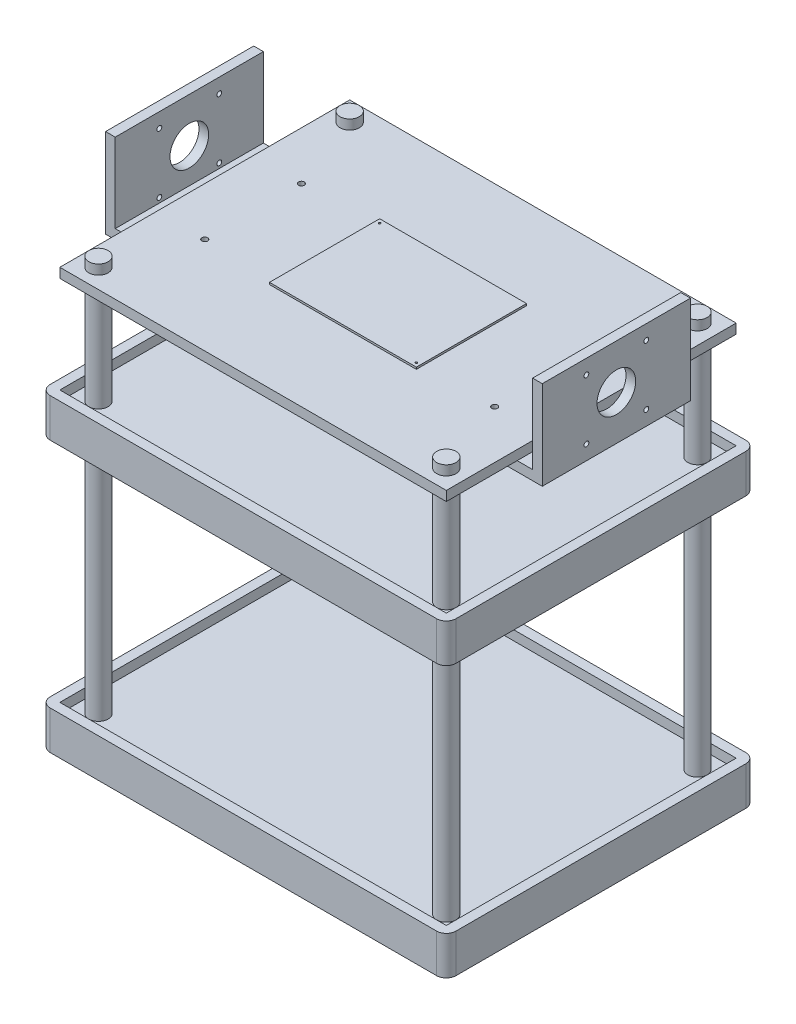
SolidWorks part; units mm, degrees
ref_plane "Front Plane" through (0, 0, 0) normal (0, 0, 1) x (1, 0, 0)
ref_plane "Top Plane" through (0, 0, 0) normal (0, 1, 0) x (1, 0, 0)
ref_plane "Right Plane" through (0, 0, 0) normal (1, 0, 0) x (0, 0, -1)
sketch "Sketch1" plane through (0, 0, 0) normal (0, 1, 0) x (1, 0, 0)
  line L1 (-100, 75) -> (100, 75)
  line L2 (-100, 75) -> (-100, -75)
  line L3 (-100, -75) -> (100, -75)
  line L4 (100, 75) -> (100, -75)
  line L5 (-100, 75) -> (100, -75) construction
  line L6 (-100, -75) -> (100, 75) construction
  point P0 (0, 0)
  dimension "D1" = 200
  dimension "D2" = 150
extrude "Boss-Extrude1" add sketch "Sketch1" along normal blind 5
sketch "Sketch2" plane through (0, 5, 0) normal (0, 1, 0) x (1, 0, 0)
  line L0 (-100, 75) -> (-100, -75) construction
  line L1 (100, 75) -> (-100, 75) construction
  line L2 (0, 73.0671) -> (0, 83.6614) construction
  line L3 (0, 83.6614) -> (0, -94.4748) construction
  line L4 (-110.8687, 0) -> (113.9791, 0) construction
  circle A0 centre (-90, 65) radius 5
  circle A1 centre (90, 65) radius 5
  circle A2 centre (90, -65) radius 5
  circle A3 centre (-90, -65) radius 5
  dimension "D1" = 10
  dimension "D2" = 10
  dimension "D3" = 10
extrude "Cut-Extrude1" cut sketch "Sketch2" against normal blind 10
ref_plane "Plane1" through (0, 140, 0) normal (0, 1, 0) x (1, 0, 0)
sketch "Sketch3" plane through (0, 140, 0) normal (0, 1, 0) x (1, 0, 0)
  line L1 (-100, 75) -> (100, 75)
  line L2 (-100, 75) -> (-100, -75)
  line L3 (-100, -75) -> (100, -75)
  line L4 (100, 75) -> (100, -75)
  line L5 (-100, 75) -> (100, -75) construction
  line L6 (-100, -75) -> (100, 75) construction
  circle A0 centre (-90, 65) radius 5
  circle A1 centre (90, 65) radius 5
  circle A2 centre (-90, -65) radius 5
  circle A3 centre (90, -65) radius 5
  point P0 (0, 0)
extrude "Boss-Extrude2" add sketch "Sketch3" along normal blind 5 separate body
ref_plane "Plane4" through (0, 200, 0) normal (0, 1, 0) x (1, 0, 0)
sketch "Sketch4" plane through (0, 200, 0) normal (0, 1, 0) x (1, 0, 0)
  line L1 (-100, 75) -> (100, 75)
  line L2 (-100, 75) -> (-100, -75)
  line L3 (-100, -75) -> (100, -75)
  line L4 (100, 75) -> (100, -75)
  line L5 (-100, 75) -> (100, -75) construction
  line L6 (-100, -75) -> (100, 75) construction
  circle A0 centre (-90, 65) radius 5
  circle A1 centre (90, 65) radius 5
  circle A2 centre (90, -65) radius 5
  circle A3 centre (-90, -65) radius 5
  point P1 (0, 0)
extrude "Boss-Extrude3" add sketch "Sketch4" along normal blind 5 separate body
sketch "Sketch5" plane through (0, 205, 0) normal (0, 1, 0) x (1, 0, 0)
  circle A0 centre (-90, -65) radius 5
sketch "Sketch17" plane through (0, 200, 0) normal (0, -1, 0) x (1, 0, 0)
  circle A0 centre (-90, -65) radius 5.3637
sketch "Sketch21" plane through (0, 5, 0) normal (0, 1, 0) x (1, 0, 0)
  circle A0 centre (-90, -65) radius 5
  circle A1 centre (-90, 65) radius 5
  circle A2 centre (90, 65) radius 5
  circle A3 centre (90, -65) radius 5
  dimension "D1" = 10
  dimension "D2" = 10
  dimension "D3" = 10
  dimension "D4" = 10
extrude "Boss-Extrude13" add sketch "Sketch21" along normal blind 205
sketch "Sketch22" plane through (0, 5, 0) normal (0, 1, 0) x (1, 0, 0)
  circle A0 centre (-90, 65) radius 5
  circle A1 centre (-90, -65) radius 5
  circle A2 centre (90, -65) radius 5
  circle A3 centre (90, 65) radius 5
  dimension "D1" = 10
  dimension "D2" = 10
  dimension "D3" = 10
  dimension "D4" = 10
extrude "Boss-Extrude14" add sketch "Sketch22" against normal blind 15
sketch "Sketch23" plane through (0, 205, 0) normal (0, 1, 0) x (1, 0, 0)
  line L0 (-100, 75) -> (-100, -75) construction
  line L1 (-140.155, 0) -> (119.4256, 0) construction
  line L2 (0, -2.75) -> (0, 2.75) construction
  circle A0 centre (-75, 25) radius 1.5
  circle A1 centre (-75, -25) radius 1.5
  circle A2 centre (75, -25) radius 1.5
  circle A3 centre (75, 25) radius 1.5
  dimension "D1" = 3
  dimension "D2" = 25
  dimension "D3" = 25
extrude "Cut-Extrude2" cut sketch "Sketch23" against normal blind 10
sketch "Sketch27" plane through (0, 205, 0) normal (0, 1, 0) x (1, 0, 0)
  line L0 (-38, 28.5) -> (38, -28.5) construction
  line L5 (-38, -28.5) -> (38, 28.5) construction
  line L7 (-38, 28.5) -> (38, 28.5)
  line L8 (-38, 28.5) -> (-38, -28.5)
  line L9 (-38, -28.5) -> (38, -28.5)
  line L10 (38, 28.5) -> (38, -28.5)
  circle A0 centre (-36, 26.5) radius 0.5
  circle A1 centre (36, -26.5) radius 0.5
  point P0 (-6.164, -10.787)
  point P5 (0, 0)
  point P11 (0, 0)
  dimension "D3" = 1
  dimension "D6" = 1
  dimension "D1" = 57
  dimension "D2" = 76
  dimension "D4" = 2
  dimension "D5" = 2
  dimension "D7" = 2
  dimension "D8" = 2
extrude "Boss-Extrude16" add sketch "Sketch27" along normal blind 1 contours L8 L7 L10 L9
sketch "Sketch30" plane through (0, 206, 0) normal (0, 1, 0) x (1, 0, 0)
  line L0 (-38, 28.5) -> (-38, -28.5) construction
  line L1 (-38, 28.5) -> (38, 28.5) construction
  line L2 (38, 28.5) -> (38, -28.5) construction
  line L3 (-38, -28.5) -> (38, -28.5) construction
  circle A0 centre (-36, 26.5) radius 0.5
  circle A1 centre (36, -26.5) radius 0.5
  dimension "D1" = 1
  dimension "D4" = 1
  dimension "D2" = 2
  dimension "D3" = 2
  dimension "D5" = 2
  dimension "D6" = 2
extrude "Cut-Extrude3" cut sketch "Sketch30" against normal blind 30
sketch "Sketch35" plane through (0, 0, 0) normal (0, -1, 0) x (-1, 0, 0)
  line L1 (100, -75) -> (-100, -75)
  line L2 (100, -75) -> (100, 75)
  line L3 (100, 75) -> (-100, 75)
  line L4 (-100, -75) -> (-100, 75)
  line L5 (100, -75) -> (-100, 75) construction
  line L6 (100, 75) -> (-100, -75) construction
  line L7 (105, -80) -> (-105, -80)
  line L8 (105, -80) -> (105, 80)
  line L9 (105, 80) -> (-105, 80)
  line L10 (-105, -80) -> (-105, 80)
  line L11 (105, -80) -> (-105, 80) construction
  line L12 (105, 80) -> (-105, -80) construction
  point P0 (0, 0)
  point P6 (0, 0)
  dimension "D1" = 150
  dimension "D2" = 160
  dimension "D3" = 200
  dimension "D4" = 210
extrude "Boss-Extrude19" add sketch "Sketch35" along normal mid plane 20 separate body
fillet "Fillet4" radius 5 4 edges at (105, 0, 80) (105, 0, -80) (-105, 0, 80) (-105, 0, -80)
sketch "Sketch39" plane through (0, 140, 0) normal (0, -1, 0) x (1, 0, 0)
  line L1 (-100, 75) -> (100, 75)
  line L2 (-100, 75) -> (-100, -75)
  line L3 (-100, -75) -> (100, -75)
  line L4 (100, 75) -> (100, -75)
  line L5 (-100, 75) -> (100, -75) construction
  line L6 (-100, -75) -> (100, 75) construction
  line L7 (-105, 80) -> (105, 80)
  line L8 (-105, 80) -> (-105, -80)
  line L9 (-105, -80) -> (105, -80)
  line L10 (105, 80) -> (105, -80)
  line L11 (-105, 80) -> (105, -80) construction
  line L12 (-105, -80) -> (105, 80) construction
  point P0 (0, 0)
  point P6 (0, 0)
  dimension "D1" = 150
  dimension "D2" = 200
  dimension "D3" = 160
  dimension "D4" = 210
extrude "Boss-Extrude20" add sketch "Sketch39" along normal mid plane 20 separate body
fillet "Fillet5" radius 5 4 edges at (105, 140, 80) (105, 140, -80) (-105, 140, -80) (-105, 140, 80)
sketch "Sketch42" plane through (0, 200, 0) normal (0, -1, 0) x (1, 0, 0)
  line L1 (-7.5, 10) -> (7.5, 10)
  line L2 (-7.5, 10) -> (-7.5, -10)
  line L3 (-7.5, -10) -> (7.5, -10)
  line L4 (7.5, 10) -> (7.5, -10)
  line L5 (-7.5, 10) -> (7.5, -10) construction
  line L6 (-7.5, -10) -> (7.5, 10) construction
  line L7 (-70.7403, -17.1967) -> (-45.7403, -17.1967)
  line L8 (-70.7403, -17.1967) -> (-70.7403, 32.8033)
  line L9 (-70.7403, 32.8033) -> (-45.7403, 32.8033)
  line L10 (-45.7403, -17.1967) -> (-45.7403, 32.8033)
  line L11 (-70.7403, -17.1967) -> (-45.7403, 32.8033) construction
  line L12 (-70.7403, 32.8033) -> (-45.7403, -17.1967) construction
  line L13 (15.7, 23.8618) -> (59, 23.8618)
  line L14 (15.7, 23.8618) -> (15.7, -19.4382)
  line L15 (15.7, -19.4382) -> (59, -19.4382)
  line L16 (59, 23.8618) -> (59, -19.4382)
  line L17 (15.7, 23.8618) -> (59, -19.4382) construction
  line L18 (15.7, -19.4382) -> (59, 23.8618) construction
  point P0 (0, 0)
  point P6 (-58.2403, 7.8033)
  point P11 (37.35, 2.2118)
  dimension "D1" = 20
  dimension "D2" = 15
  dimension "D3" = 50
  dimension "D4" = 25
  dimension "D5" = 43.3
  dimension "D6" = 43.3
  dimension "D7" = 8.2
extrude "Boss-Extrude23" add sketch "Sketch42" along normal blind 1
sketch "Sketch46" plane through (0, 200, 0) normal (0, -1, 0) x (-1, 0, 0)
  line L0 (-196.0871, 0) -> (303.0775, 0) construction
  line L5 (100, -75) -> (100, 75) construction
  line L6 (0, 82.5) -> (0, -82.5) construction
  line L7 (-108, 38.3353) -> (-108, -38.3353)
  line L8 (78, 38.3353) -> (108, 38.3353)
  line L9 (78, 38.3353) -> (78, -38.3353)
  line L10 (78, -38.3353) -> (108, -38.3353)
  line L11 (108, 38.3353) -> (108, -38.3353)
  line L12 (78, 38.3353) -> (108, -38.3353) construction
  line L13 (78, -38.3353) -> (108, 38.3353) construction
  line L14 (-78, -38.3353) -> (-108, -38.3353)
  line L15 (-78, 38.3353) -> (-78, -38.3353)
  line L16 (-78, 38.3353) -> (-108, 38.3353)
  point P0 (122.8294, -19.1676)
  point P6 (93, 0)
  dimension "D1" = 22
  dimension "D2" = 30
extrude "Boss-Extrude24" add sketch "Sketch46" along normal blind 5
sketch "Sketch48" plane through (-108, 0, 0) normal (-1, 0, 0) x (0, 0, 1)
  line L0 (0, 195) -> (0, 241) construction
  line L1 (-38.3353, 195) -> (38.3353, 195)
  line L2 (-38.3353, 195) -> (-38.3353, 241)
  line L3 (-38.3353, 241) -> (38.3353, 241)
  line L4 (38.3353, 195) -> (38.3353, 241)
  line L5 (-38.3353, 218) -> (38.3353, 218) construction
  line L6 (38.3353, 195) -> (38.3353, 200) construction
  circle A0 centre (-15.5, 202.5) radius 1.25
  circle A1 centre (15.5, 202.5) radius 1.25
  circle A2 centre (15.5, 233.5) radius 1.25
  circle A3 centre (-15.5, 233.5) radius 1.25
  circle A4 centre (0, 218) radius 10
  dimension "D2" = 2.5
  dimension "D3" = 2.5
  dimension "D8" = 20
  dimension "D1" = 7.5
  dimension "D4" = 15.5
  dimension "D5" = 15.5
  dimension "D6" = 31
  dimension "D7" = 15.5
extrude "Boss-Extrude25" add sketch "Sketch48" along normal blind 5
sketch "Sketch54" plane through (108, 0, 0) normal (1, 0, 0) x (0, 0, -1)
  line L1 (-38.3353, 195) -> (38.3353, 195)
  line L2 (-38.3353, 195) -> (-38.3353, 241)
  line L3 (-38.3353, 241) -> (38.3353, 241)
  line L4 (38.3353, 195) -> (38.3353, 241)
extrude "Boss-Extrude26" add sketch "Sketch54" along normal blind 5
ref_plane "Plane5" through (0, 65, 0) normal (0, 1, 0) x (1, 0, 0)
sketch "Sketch55" plane through (113, 0, 0) normal (1, 0, 0) x (0, 0, -1)
  line L0 (-38.3353, 218) -> (38.3353, 218) construction
  line L1 (-38.3353, 241) -> (-38.3353, 195) construction
  line L2 (38.3353, 195) -> (38.3353, 241) construction
  line L3 (0, 195) -> (0, 241) construction
  line L4 (-38.3353, 195) -> (38.3353, 195) construction
  line L5 (38.3353, 241) -> (-38.3353, 241) construction
  circle A0 centre (-15.5, 202.5) radius 1.25
  circle A1 centre (15.5, 202.5) radius 1.25
  circle A2 centre (15.5, 233.5) radius 1.25
  circle A3 centre (-15.5, 233.5) radius 1.25
  circle A4 centre (0, 218) radius 10
  dimension "D1" = 2.5
  dimension "D2" = 2.5
  dimension "D7" = 20
  dimension "D3" = 15.5
  dimension "D4" = 15.5
  dimension "D5" = 15.5
  dimension "D6" = 15.5
extrude "Cut-Extrude4" cut sketch "Sketch55" against normal blind 10
